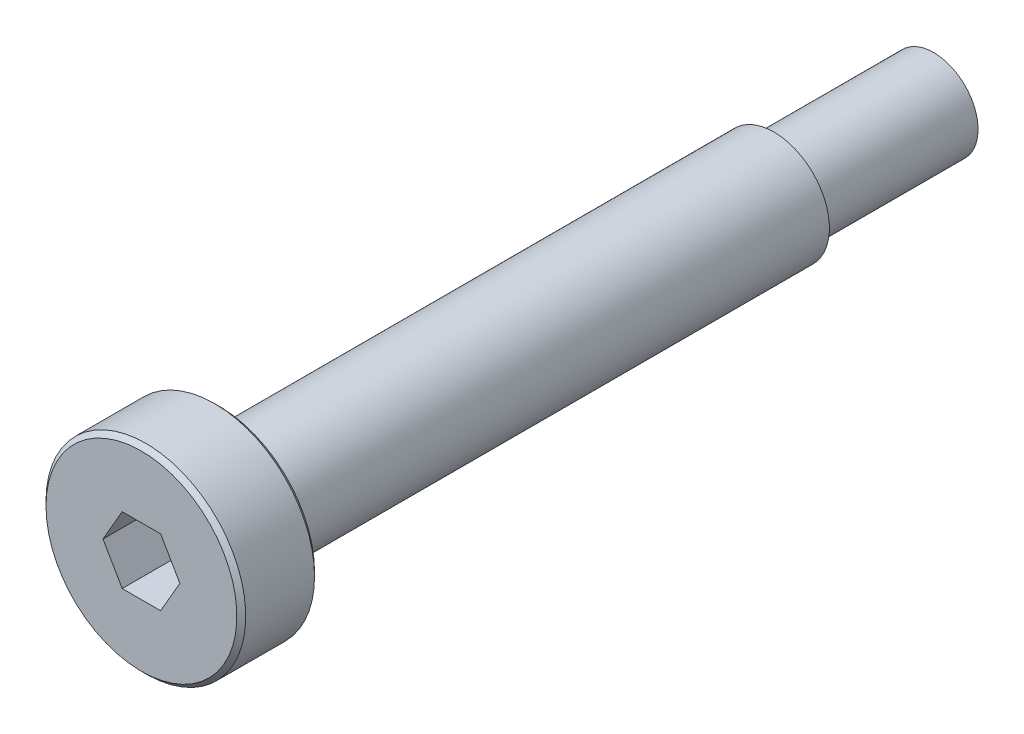
SolidWorks part; units mm, degrees
material "AISI 304"
ref_plane "前视基准面" through (0, 0, 0) normal (1, 0, 0) x (0, 1, 0)
ref_plane "上视基准面" through (0, 0, 0) normal (0, 0, 1) x (0, 1, 0)
ref_plane "右视基准面" through (0, 0, 0) normal (0, 1, 0) x (-1, 0, 0)
other "Configuration Table"
sketch "草图1" plane through (0, 0, 0) normal (1, 0, 0) x (0, 1, 0)
  line L0 (0, 0) -> (-4.5, 0)
  line L1 (-4.5, 0) -> (-4.5, -3.5)
  line L2 (-4.5, -3.5) -> (-2.5, -3.5)
  line L3 (-2.5, -3.5) -> (-2.5, -28.5)
  line L4 (-2.5, -28.5) -> (-2, -28.5)
  line L5 (-2, -28.5) -> (-2, -35.7)
  line L6 (-2, -35.7) -> (0, -35.7)
  line L7 (0, -35.7) -> (0, 0)
  point P8 (-2.25, -28.5)
  dimension "D1" = 3.5
  dimension "D2" = 25
  dimension "D3" = 7.2
  dimension "D4" = 2
  dimension "D5" = 4.5
  dimension "D6" = 2.5
revolve "旋转1" add sketch "草图1" angle 360 about L7
cosmetic thread "装饰螺纹线1" parameters "D2"=3
sketch "草图2" plane through (0, 0, 0) normal (0, 0, 1) x (1, 0, 0)
  line L0 (0, 0) -> (1.7321, 0) construction
  line L1 (1.7321, 0) -> (0.866, 1.5)
  line L2 (0.866, 1.5) -> (-0.866, 1.5)
  line L3 (-0.866, 1.5) -> (-1.7321, 0)
  line L4 (-1.7321, 0) -> (-0.866, -1.5)
  line L5 (-0.866, -1.5) -> (0.866, -1.5)
  line L6 (0.866, -1.5) -> (1.7321, 0)
  circle A0 centre (0, 0) radius 1.5 construction
  dimension "D1" = 3
extrude "切除-拉伸1" cut sketch "草图2" against normal blind 3
chamfer "倒角1" distance 0.2 angle 45 2 edges at (-4.5, 0, -3.5) (-4.5, 0, 0)
